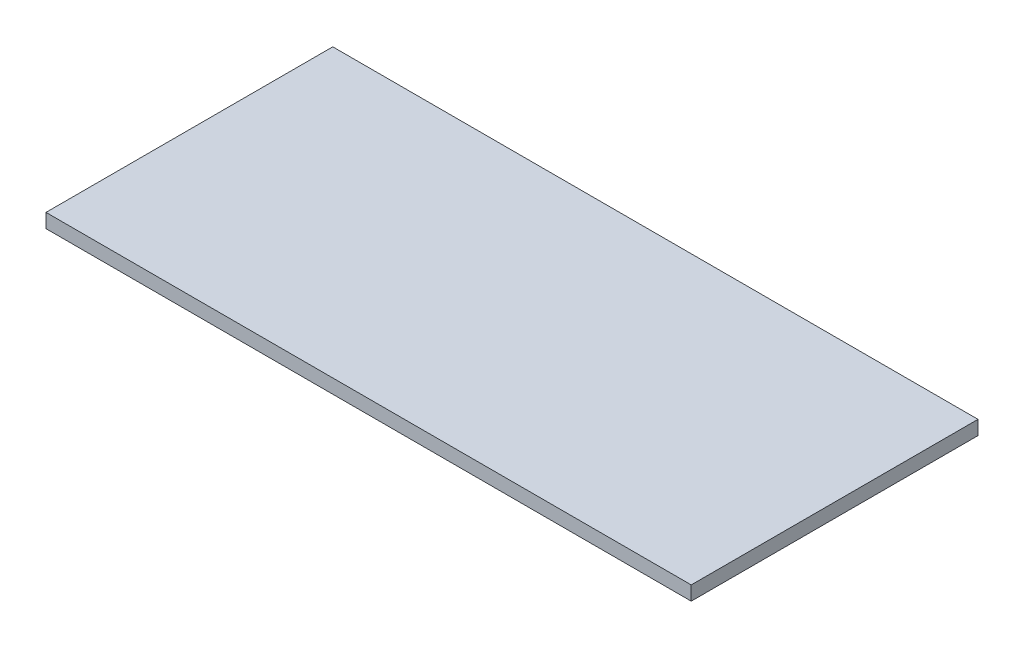
SolidWorks part; units mm, degrees
material "PMMA"
ref_plane "Front Plane" through (0, 0, 0) normal (0, 0, 1) x (1, 0, 0)
ref_plane "Top Plane" through (0, 0, 0) normal (0, 1, 0) x (1, 0, 0)
ref_plane "Right Plane" through (0, 0, 0) normal (1, 0, 0) x (0, 0, -1)
sketch "Sketch1" plane through (0, 0, 0) normal (0, 1, 0) x (1, 0, 0)
  line L1 (-114.3, -50.8) -> (114.3, -50.8)
  line L2 (-114.3, -50.8) -> (-114.3, 50.8)
  line L3 (-114.3, 50.8) -> (114.3, 50.8)
  line L4 (114.3, -50.8) -> (114.3, 50.8)
  line L5 (-114.3, -50.8) -> (114.3, 50.8) construction
  line L6 (-114.3, 50.8) -> (114.3, -50.8) construction
  point P0 (0, 0)
  dimension "D1" = 228.6
  dimension "D2" = 101.6
extrude "Boss-Extrude1" add sketch "Sketch1" along normal blind 5
